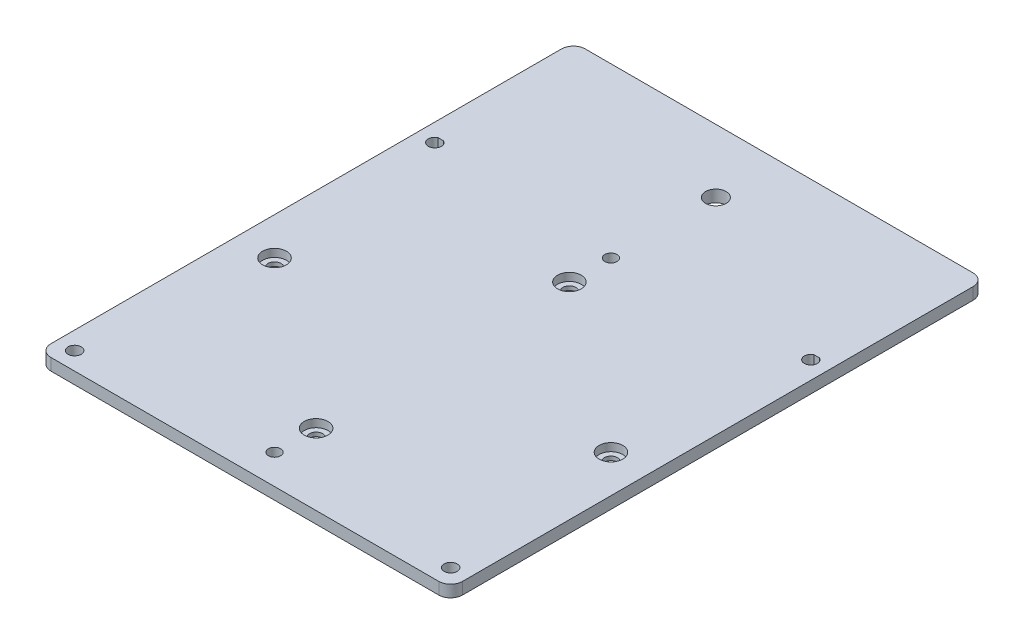
SolidWorks part; units mm, degrees
ref_plane "前视基准面" through (0, 0, 0) normal (0, 0, 1) x (1, 0, 0)
ref_plane "上视基准面" through (0, 0, 0) normal (0, 1, 0) x (1, 0, 0)
ref_plane "右视基准面" through (0, 0, 0) normal (1, 0, 0) x (0, 0, -1)
ref_plane "基准面4" through (0, 0, 0) normal (0, -1, 0) x (1, 0, 0)
sketch "草图1" plane through (0, 0, 0) normal (0, -1, 0) x (1, 0, 0)
  line L0 (0, 0) -> (104, 0)
  line L1 (104, 0) -> (104, 100)
  line L2 (104, 100) -> (0, 100)
  line L3 (0, 100) -> (0, 0)
extrude "凸台-拉伸1" add sketch "草图1" against normal blind 3
hole_wizard "Ø3.3 (3.3) 直径孔1" positions "草图46" profile "草图45" hole size "Ø3.3" standard "ANSI Metric"
sketch "草图46" plane through (0, 0, 0) normal (0, -1, 0) x (-1, 0, 0)
  point P0 (-4.5, -4.5)
  point P1 (-99.5, -4.5)
  point P2 (-99.5, -95.5)
  point P3 (-4.5, -95.5)
sketch "草图45" plane through (4.5, 0, 4.5) normal (1, 0, 0) x (0, 0, -1)
  line L0 (0, 0) -> (0, 3)
  line L1 (0, 3) -> (1.65, 3)
  line L2 (1.65, 3) -> (1.65, 0)
  line L5 (1.65, 0) -> (0, 0)
  line L11 (0, -6.35) -> (0, 107.95) construction
  dimension "通孔孔直径" = 3.3
  dimension "通孔孔深度" = 3
hole_wizard "M3 六角头机械螺钉的柱形沉头孔1" positions "草图48" profile "草图47" counterbore size "M3" standard "ANSI Metric"
sketch "草图48" plane through (0, 3, 0) normal (0, 1, 0) x (1, 0, 0)
  line L0 (52, -18) -> (52, -82) construction
  line L2 (9.5, -50) -> (94.5, -50) construction
  point P0 (52, -18)
  point P1 (94.5, -50)
  point P2 (9.5, -50)
  point P3 (52, -82)
sketch "草图47" plane through (52, 3, 18) normal (1, 0, 0) x (0, 0, 1)
  line L0 (0, 0) -> (0, 3)
  line L1 (0, 3) -> (1.65, 3)
  line L3 (1.65, 3) -> (1.65, 2)
  line L4 (1.65, 2) -> (3, 2)
  line L5 (3, 2) -> (3, 0)
  line L7 (3, 0) -> (0, 0)
  line L11 (0, -6.35) -> (0, 107.95) construction
  dimension "通孔孔直径" = 3.3
  dimension "通孔孔深度" = 3
  dimension "柱形沉头孔直径" = 6
  dimension "柱形沉头孔深度" = 2
fillet "圆角1" radius 3 4 edges at (104, 1.5, 0) (104, 1.5, 100) (0, 1.5, 0) (0, 1.5, 100)
sketch "草图49" plane through (0, 3, 0) normal (0, 1, 0) x (1, 0, 0)
  line L0 (52, -18) -> (52, -50018) construction
  line L1 (9.5, -50) -> (94.5, -50) construction
  circle A0 centre (52, -7.5) radius 1.55
  circle A1 centre (52, -92.5) radius 1.55
  dimension "D1" = 3.1
  dimension "D2" = 42.5
extrude "切除-拉伸44" cut sketch "草图49" against normal through all
sketch "草图50" plane through (0, 3, 0) normal (0, 1, 0) x (1, 0, 0)
  line L1 (0, -3) -> (104, -3)
  line L2 (0, -3) -> (0, 35)
  line L3 (0, 35) -> (104, 35)
  line L4 (104, -3) -> (104, 35)
  line L5 (104, -3) -> (104, -97) construction
  line L6 (3, 0) -> (101, 0) construction
  dimension "D1" = 35
extrude "凸台-拉伸2" add sketch "草图50" against normal up to surface (3 mm away) up to face at (52, 0, 9.05)
sketch "草图51" plane through (0, 3, 0) normal (0, 1, 0) x (1, 0, 0)
  line L0 (52, -18) -> (52, 30.0109) construction
  circle A3 centre (52, 19) radius 2.6
  dimension "D1" = 37
  dimension "D2" = 5.2
extrude "切除-拉伸45" cut sketch "草图51" against normal through all
fillet "圆角2" radius 3 2 edges at (104, 1.5, -35) (0, 1.5, -35)
